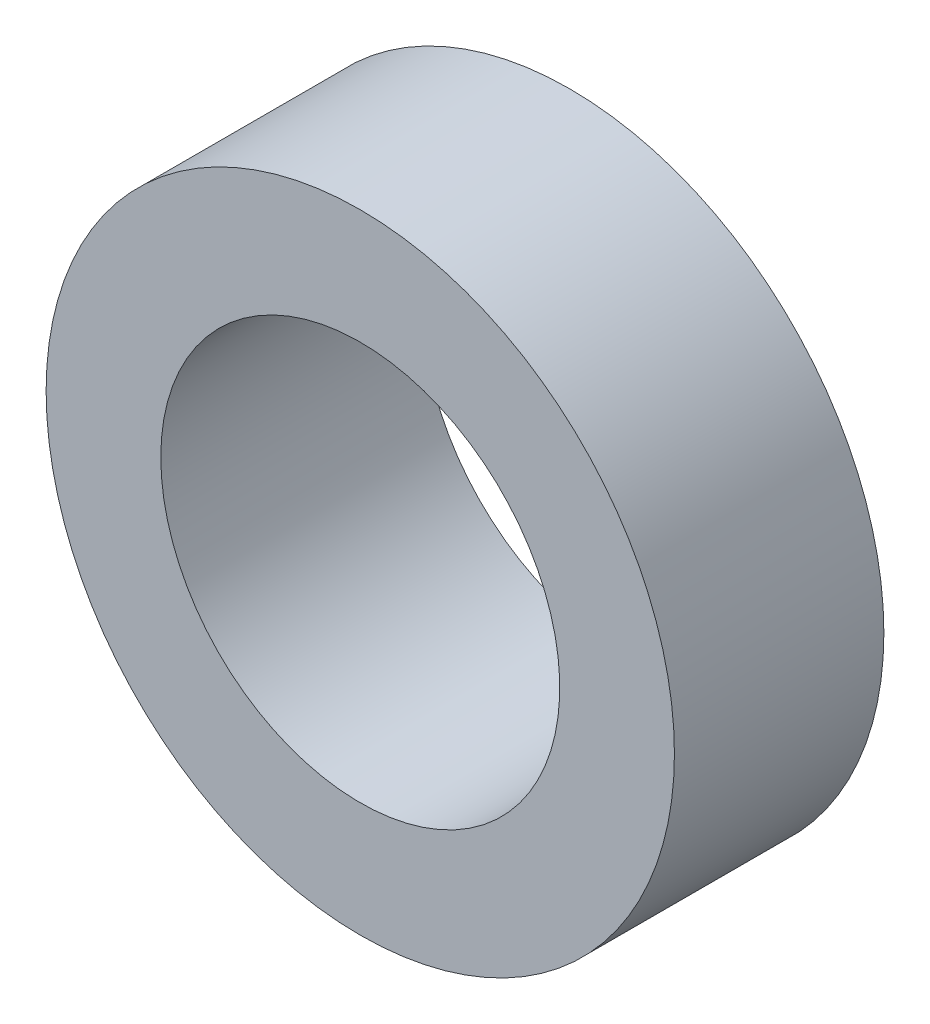
SolidWorks part; units mm, degrees
material "ABS"
ref_plane "Alzado" through (0, 0, 0) normal (0, 0, 1) x (1, 0, 0)
ref_plane "Planta" through (0, 0, 0) normal (0, 1, 0) x (1, 0, 0)
ref_plane "Vista lateral" through (0, 0, 0) normal (1, 0, 0) x (0, 0, -1)
sketch "Croquis1" plane through (0, 0, 0) normal (0, 0, 1) x (1, 0, 0)
  circle A0 centre (0, 0) radius 23.05
extrude "Saliente-Extruir1" add sketch "Croquis1" along normal blind 25
sketch "Croquis2" plane through (0, 0, 0) normal (0, 0, -1) x (-1, 0, 0)
  circle A0 centre (0, 0) radius 19.05
extrude "Cortar-Extruir1" cut sketch "Croquis2" against normal blind 29
sketch "Croquis3" plane through (0, 0, 0) normal (0, 0, -1) x (-1, 0, 0)
  circle A0 centre (0, 0) radius 20.5
  circle A1 centre (0, 0) radius 23.05
extrude "Cortar-Extruir2" cut sketch "Croquis3" against normal blind 5
sketch "Croquis4" plane through (0, 0, 25) normal (0, 0, 1) x (1, 0, 0)
  circle A0 centre (0, 0) radius 30
extrude "Saliente-Extruir3" add sketch "Croquis4" against normal blind 20
sketch "Croquis5" plane through (0, 0, 5) normal (0, 0, -1) x (-1, 0, 0)
  circle A0 centre (0, 0) radius 19.05
extrude "Cortar-Extruir3" cut sketch "Croquis5" against normal blind 20
